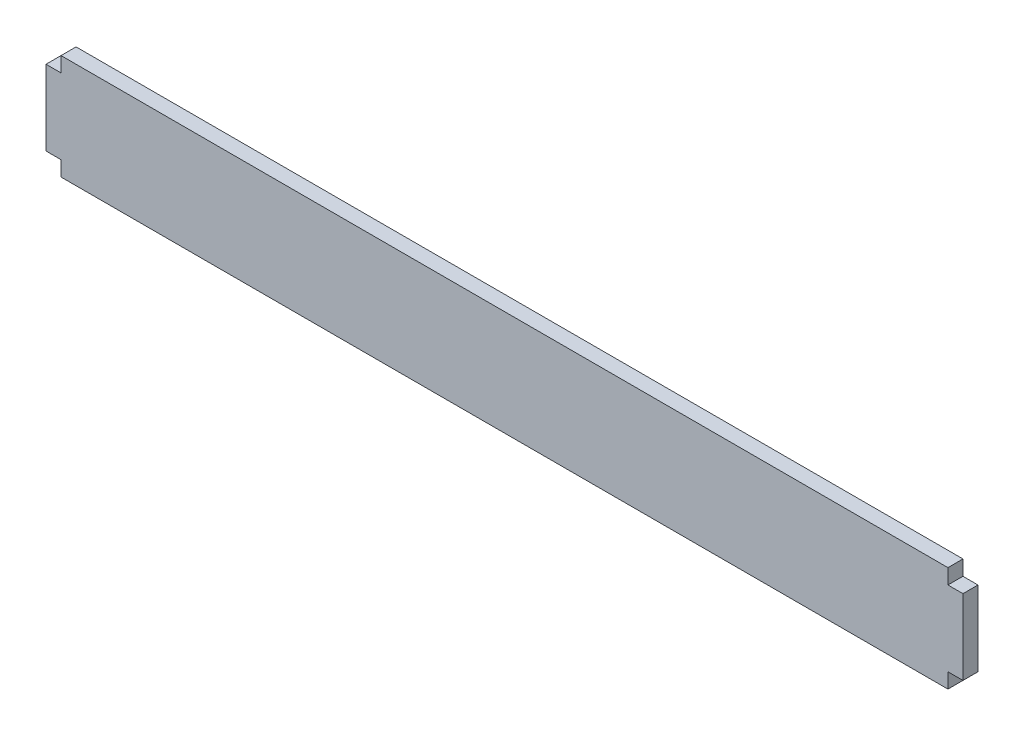
SolidWorks part; units mm, degrees
ref_plane "Front Plane" through (0, 0, 0) normal (0, 0, 1) x (1, 0, 0)
ref_plane "Top Plane" through (0, 0, 0) normal (0, 1, 0) x (1, 0, 0)
ref_plane "Right Plane" through (0, 0, 0) normal (1, 0, 0) x (0, 0, -1)
sketch "Sketch1" plane through (0, 0, 0) normal (0, 0, 1) x (1, 0, 0)
  line L0 (-147.5, 35) -> (-147.5, 58.0915) construction
  line L1 (0, 0) -> (-295, 0)
  line L2 (0, 0) -> (0, 35)
  line L3 (0, 35) -> (-295, 35)
  line L4 (-295, 0) -> (-295, 35)
  line L5 (-295, 5) -> (-300, 5)
  line L6 (-295, 5) -> (-295, 30)
  line L7 (-295, 30) -> (-300, 30)
  line L8 (-300, 5) -> (-300, 30)
  line L9 (0, 30) -> (5, 30)
  line L10 (5, 5) -> (5, 30)
  line L11 (0, 5) -> (5, 5)
  line L12 (0, 5) -> (0, 30)
  dimension "D1" = 295
  dimension "D2" = 35
  dimension "D3" = 5
  dimension "D4" = 5
  dimension "D5" = 25
extrude "Boss-Extrude1" add sketch "Sketch1" along normal blind 5 contours L4 L1 L2 L3 | L8 L5 L4 L7 | L2 L11 L10 L9
